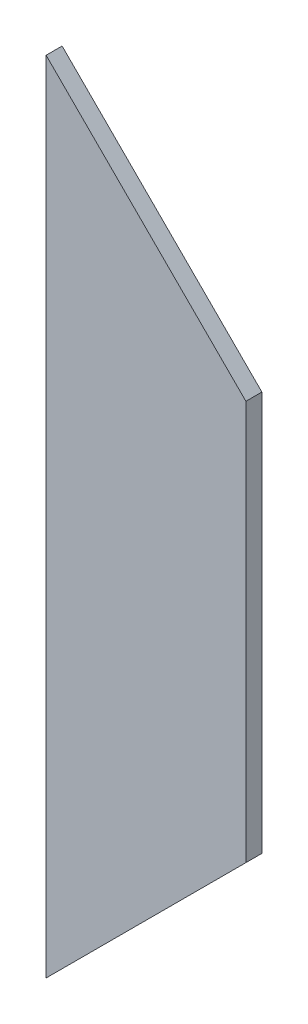
SolidWorks part; units mm, degrees
material "Сосна"
ref_plane "Спереди" through (0, 0, 0) normal (0, 0, 1) x (1, 0, 0)
ref_plane "Сверху" through (0, 0, 0) normal (0, 1, 0) x (1, 0, 0)
ref_plane "Справа" through (0, 0, 0) normal (1, 0, 0) x (0, 0, -1)
sketch "Эскиз1" plane through (0, 0, 0) normal (0, 0, 1) x (1, 0, 0)
  line L0 (0, 0) -> (0, 200)
  line L1 (0, 0) -> (50, 50)
  line L2 (50, 50) -> (50, 150)
  line L3 (50, 150) -> (0, 200)
  dimension "D1" = 200
  dimension "D2" = 50
  dimension "D3" = 45
  dimension "D4" = 45
extrude "Бобышка-Вытянуть1" add sketch "Эскиз1" along normal blind 4
